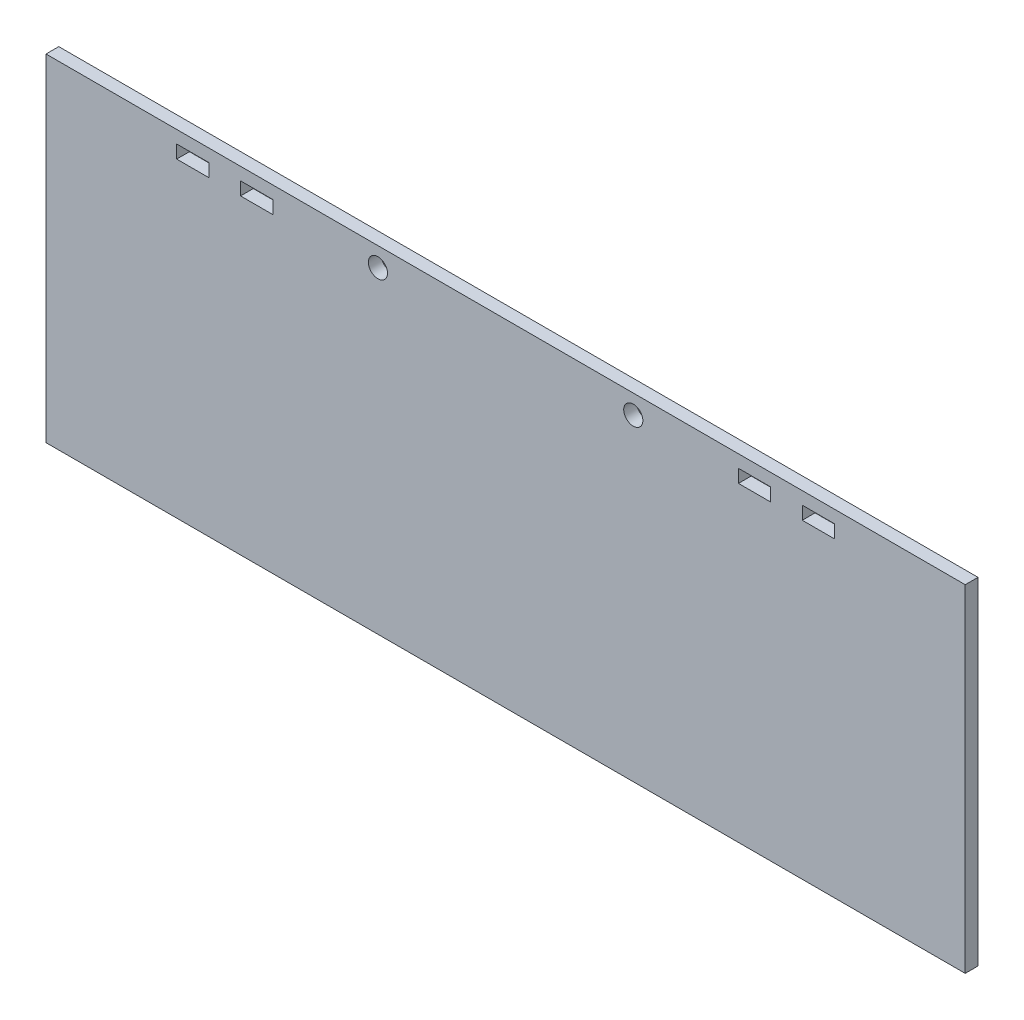
SolidWorks part; units mm, degrees
ref_plane "前视基准面" through (0, 0, 0) normal (0, 0, 1) x (1, 0, 0)
ref_plane "上视基准面" through (0, 0, 0) normal (0, 1, 0) x (1, 0, 0)
ref_plane "右视基准面" through (0, 0, 0) normal (1, 0, 0) x (0, 0, -1)
sketch "草图1" plane through (0, 0, 0) normal (0, 0, 1) x (1, 0, 0)
  line L4 (15.275, -1.025) -> (34.275, -1.025) construction
  line L5 (15.275, -1.025) -> (5.275, -1.025) construction
  line L11 (12.75, 0) -> (17.8, 0)
  line L12 (12.75, 0) -> (12.75, -2.05)
  line L13 (12.75, -2.05) -> (17.8, -2.05)
  line L27 (-17.7231, 1.9731) -> (-17.7231, -50.7609)
  line L28 (126.2769, 1.9731) -> (126.2769, -50.7609)
  line L31 (17.8, 0) -> (17.8, -2.05)
  line L32 (12.75, 0) -> (17.8, -2.05) construction
  line L33 (12.75, -2.05) -> (17.8, 0) construction
  line L36 (2.75, 0) -> (7.8, 0)
  line L37 (2.75, 0) -> (2.75, -2.05)
  line L38 (2.75, -2.05) -> (7.8, -2.05)
  line L39 (7.8, 0) -> (7.8, -2.05)
  line L40 (2.75, 0) -> (7.8, -2.05) construction
  line L41 (2.75, -2.05) -> (7.8, 0) construction
  line L42 (34.275, -1.025) -> (74.275, -1.025) construction
  line L43 (54.275, -1.025) -> (54.275, -5.3567) construction
  line L44 (105.8, -2.05) -> (100.75, 0) construction
  line L45 (105.8, 0) -> (100.75, -2.05) construction
  line L46 (95.8, -2.05) -> (90.75, 0) construction
  line L47 (95.8, 0) -> (90.75, -2.05) construction
  line L48 (93.275, -1.025) -> (103.275, -1.025) construction
  line L49 (93.275, -1.025) -> (74.275, -1.025) construction
  line L50 (100.75, 0) -> (100.75, -2.05)
  line L51 (105.8, -2.05) -> (100.75, -2.05)
  line L52 (105.8, 0) -> (105.8, -2.05)
  line L53 (105.8, 0) -> (100.75, 0)
  line L54 (90.75, 0) -> (90.75, -2.05)
  line L55 (95.8, -2.05) -> (90.75, -2.05)
  line L56 (95.8, 0) -> (95.8, -2.05)
  line L57 (95.8, 0) -> (90.75, 0)
  line L59 (-17.7231, -50.7609) -> (126.2769, -50.7609)
  line L61 (75.7854, -1.025) -> (126.2769, -1.025) construction
  line L62 (32.775, -1.025) -> (-17.7231, -1.025) construction
  line L63 (54.2769, 1.9731) -> (54.275, -1.025) construction
  line L64 (54.2769, 1.9731) -> (126.2769, 1.9731)
  line L65 (54.2769, 1.9731) -> (-17.7231, 1.9731)
  circle A0 centre (34.275, -1.025) radius 1.5
  circle A2 centre (74.275, -1.025) radius 1.5
extrude "凸台-拉伸1" add sketch "草图1" along normal blind 2
